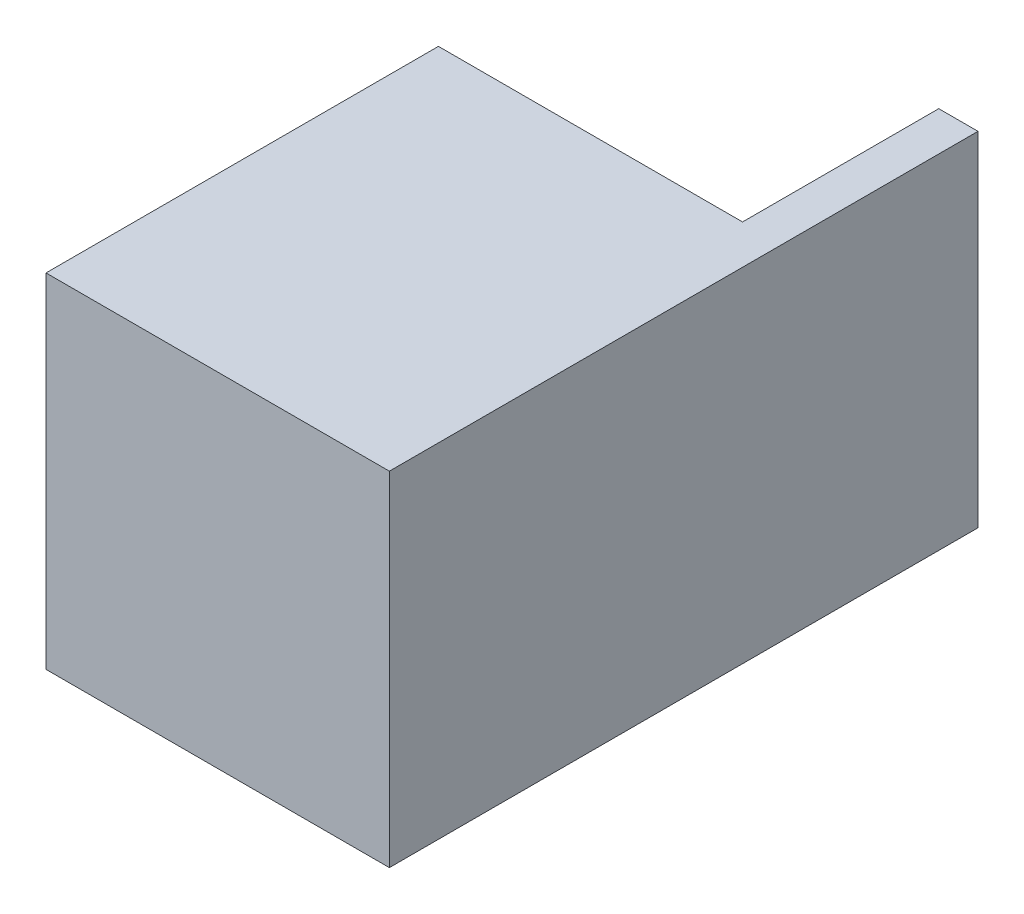
SolidWorks part; units mm, degrees
ref_plane "Alzado" through (0, 0, 0) normal (0, 0, 1) x (1, 0, 0)
ref_plane "Planta" through (0, 0, 0) normal (0, 1, 0) x (1, 0, 0)
ref_plane "Vista lateral" through (0, 0, 0) normal (1, 0, 0) x (0, 0, -1)
sketch "Croquis1" plane through (0, 0, 0) normal (0, 0, 1) x (1, 0, 0)
  line L1 (-17.5, 17.5) -> (17.5, 17.5)
  line L2 (-17.5, 17.5) -> (-17.5, -17.5)
  line L3 (-17.5, -17.5) -> (17.5, -17.5)
  line L4 (17.5, 17.5) -> (17.5, -17.5)
  line L5 (-17.5, 17.5) -> (17.5, -17.5) construction
  line L6 (-17.5, -17.5) -> (17.5, 17.5) construction
  point P0 (0, 0)
  dimension "D1" = 35
  dimension "D2" = 35
extrude "Saliente-Extruir1" add sketch "Croquis1" along normal blind 40
sketch "Croquis4" plane through (0, 0, 0) normal (0, 0, -1) x (-1, 0, 0)
  line L4 (-13.5, 13.5) -> (-13.5, 17.5)
  line L5 (-17.5, 17.5) -> (17.5, 17.5) construction
  line L6 (13.5, -13.5) -> (17.5, -13.5)
  line L7 (17.5, 17.5) -> (17.5, -17.5) construction
  line L8 (-13.5, 13.5) -> (-13.5, -13.5)
  line L9 (-13.5, -13.5) -> (13.5, -13.5)
  line L10 (13.5, -13.5) -> (13.5, 13.5)
  line L11 (13.5, 13.5) -> (-13.5, 13.5)
  line L12 (-13.5, 13.5) -> (-13.5, -13.5)
  line L13 (-13.5, -13.5) -> (13.5, -13.5)
  line L16 (17.5, -13.5) -> (17.5, -17.5)
  line L17 (17.5, -17.5) -> (-17.5, -17.5)
  line L18 (-17.5, -17.5) -> (-17.5, 17.5)
  line L19 (-17.5, 17.5) -> (-13.5, 17.5)
  dimension "D1" = 4
extrude "Saliente-Extruir3" add sketch "Croquis4" along normal blind 20
